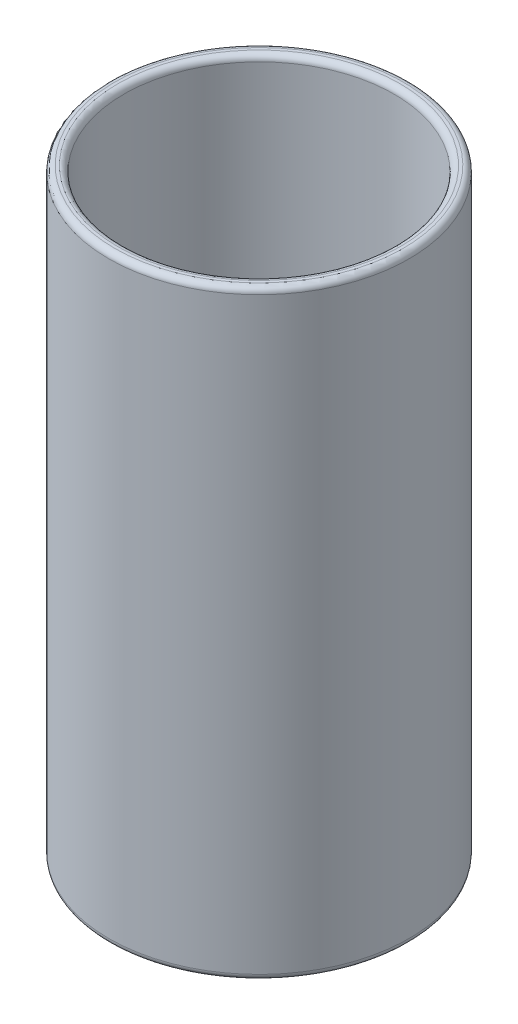
SolidWorks part; units mm, degrees
ref_plane "Front Plane" through (0, 0, 0) normal (0, 0, 1) x (1, 0, 0)
ref_plane "Top Plane" through (0, 0, 0) normal (0, 1, 0) x (1, 0, 0)
ref_plane "Right Plane" through (0, 0, 0) normal (1, 0, 0) x (0, 0, -1)
sketch "Sketch1" plane through (0, 0, 0) normal (0, 0, 1) x (1, 0, 0)
  line L0 (0, 0) -> (0, -264.2189) construction
  line L1 (0, -34.7035) -> (-50, -34.7035)
  line L2 (-50, -34.7035) -> (-50, -234.7035)
  line L3 (-50, -234.7035) -> (0, -234.7035)
  line L4 (0, -34.7035) -> (0, -234.7035)
  point P5 (0, 0)
  point P8 (0, -264.2189)
  point P9 (0, -234.7035)
  dimension "D1" = 50
  dimension "D2" = 200
revolve "Revolve1" add sketch "Sketch1" angle 360 about L0
sketch "Sketch2" plane through (0, -34.7035, 0) normal (0, 1, 0) x (1, 0, 0)
  circle A0 centre (0, 0) radius 45
  circle A1 centre (0, 0) radius 50 construction
  dimension "D1" = 5
extrude "Cut-Extrude1" cut sketch "Sketch2" against normal blind 195
fillet "Fillet2" radius 2 2 edges at (0, -34.7035, 45) (0, -34.7035, 50)
fillet "Fillet3" radius 2 1 edges at (0, -234.7035, 50)
